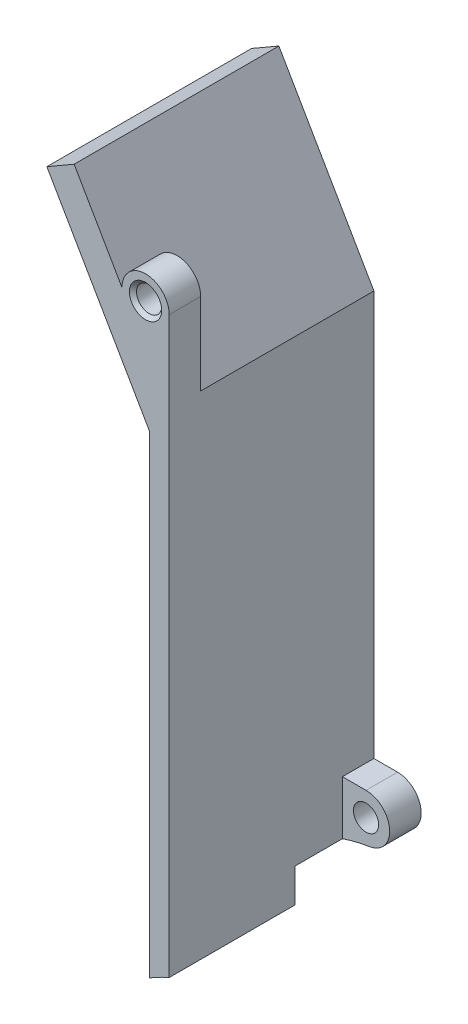
SolidWorks part; units mm, degrees
material "1060-H16"
ref_plane "前视基准面" through (0, 0, 0) normal (0, 0, 1) x (1, 0, 0)
ref_plane "上视基准面" through (0, 0, 0) normal (0, 1, 0) x (1, 0, 0)
ref_plane "右视基准面" through (0, 0, 0) normal (1, 0, 0) x (0, 0, -1)
sketch "草图1" plane through (0, 0, 0) normal (0, 0, 1) x (1, 0, 0)
  line L0 (-3.4641, -2) -> (-5.1962, -3)
  line L1 (-5.1962, -3) -> (1.3209, -14.2878)
  line L2 (1.3209, -14.2878) -> (1.3209, -44.3556)
  line L3 (2.5709, -12.4529) -> (2.5709, -43.7084)
  line L4 (2.5709, -38.4134) -> (2.5709, -44.8063) construction
  line L6 (2.5709, -12.4529) -> (-3.4641, -2)
  circle A0 centre (6.0709, -52) radius 9
  arc A1 (5.1962, 3) -> (-5.1962, -3) centre (0, 0) ccw construction
  dimension "D3" = 30.0677
  dimension "D1" = 2
  dimension "D2" = 13.0341
  dimension "D4" = 150
  dimension "D5" = 1.25
extrude "凸台-拉伸1" add sketch "草图1" against normal blind 13 from offset 2 offset against normal yes
sketch "草图2" plane through (0, 0, -15) normal (0, 0, -1) x (-1, 0, 0)
  circle A0 centre (-6.0709, -52) radius 11
extrude "切除-拉伸1" cut sketch "草图2" against normal blind 5
sketch "草图3" plane through (0, 0, -15) normal (0, 0, -1) x (-1, 0, 0)
  line L0 (-2.5709, -12.4529) -> (-2.5709, -41.5717) construction
  line L1 (-2.5709, -12.4529) -> (-2.5709, -41.5717)
  line L2 (-4.0709, -38.161) -> (-2.5709, -38.161)
  arc A0 (-1.3209, -42.0784) -> (-8.8209, -41.3493) centre (-6.0709, -52) ccw construction
  arc A1 (-1.3209, -42.0784) -> (-8.8209, -41.3493) centre (-6.0709, -52) ccw
  circle A2 centre (-4.0709, -39.661) radius 1.5
  line M2 (-2.5709, -12.4529) -> (-2.5709, -41.5717)
  dimension "D1" = 3
extrude "凸台-拉伸2" add sketch "草图3" against normal blind 2 contours A2 | A2 A1 M2 | A2 L1 L2
sketch "草图4" plane through (0, 0, -2) normal (0, 0, 1) x (1, 0, 0)
  line L0 (2.5709, -12.4529) -> (2.5709, -7.2568)
  line L1 (2.5709, -7.2568) -> (-0.4291, -7.2568)
  line L2 (2.5709, -12.4529) -> (-3.4641, -2) construction
  line L3 (-0.4291, -7.2568) -> (2.5709, -12.4529)
  circle A0 centre (1.0709, -7.2568) radius 1.5
  line M3 (2.5709, -12.4529) -> (-3.4641, -2)
  dimension "D1" = 3
extrude "凸台-拉伸3" add sketch "草图4" against normal blind 2 contours A0 L0 M3 | L3 A0 L1 | L1 A0
hole_wizard "M2 螺纹孔4" positions "草图11" profile "草图12" tap size "M2" standard "GB"
sketch "草图11" plane through (0, 0, -2) normal (0, 0, 1) x (1, 0, 0)
  point P0 (1.0709, -7.2568)
sketch "草图12" plane through (1.0709, -7.2568, -2) normal (1, 0, 0) x (0, -1, 0)
  line L0 (0, 0) -> (0, 5.6807)
  line L1 (0, 5.6807) -> (0.8, 5.2)
  line L2 (0.8, 5.2) -> (0.8, 0.225)
  line L3 (0.8, 0.225) -> (1.025, 0)
  line L5 (1.025, 0) -> (0, 0)
  line L6 (-0.8, 0.225) -> (-1.025, 0) construction
  line L10 (0, 5.6807) -> (-0.8, 5.2) construction
  line L11 (0, -6.35) -> (0, 107.95) construction
  dimension "螺纹孔钻头直径" = 1.6
  dimension "螺纹孔钻头深度" = 5.2
  dimension "近端锥形沉头孔直径" = 2.05
  dimension "近端锥形沉头孔角度" = 90
  dimension "导头角度" = 118
cosmetic thread "孔螺蚊线5" parameters "D1"=2, "D2"=2
hole_wizard "M2 螺纹孔5" positions "草图13" profile "草图14" tap size "M2" standard "GB"
sketch "草图13" plane through (0, 0, -15) normal (0, 0, -1) x (-1, 0, 0)
  point P0 (-4.0709, -39.661)
sketch "草图14" plane through (4.0709, -39.661, -15) normal (1, 0, 0) x (0, 1, 0)
  line L0 (0, 0) -> (0, 5.6807)
  line L1 (0, 5.6807) -> (0.8, 5.2)
  line L2 (0.8, 5.2) -> (0.8, 0.225)
  line L3 (0.8, 0.225) -> (1.025, 0)
  line L5 (1.025, 0) -> (0, 0)
  line L6 (-0.8, 0.225) -> (-1.025, 0) construction
  line L10 (0, 5.6807) -> (-0.8, 5.2) construction
  line L11 (0, -6.35) -> (0, 107.95) construction
  dimension "螺纹孔钻头直径" = 1.6
  dimension "螺纹孔钻头深度" = 5.2
  dimension "近端锥形沉头孔直径" = 2.05
  dimension "近端锥形沉头孔角度" = 90
  dimension "导头角度" = 118
cosmetic thread "孔螺蚊线6" parameters "D1"=2, "D2"=2
